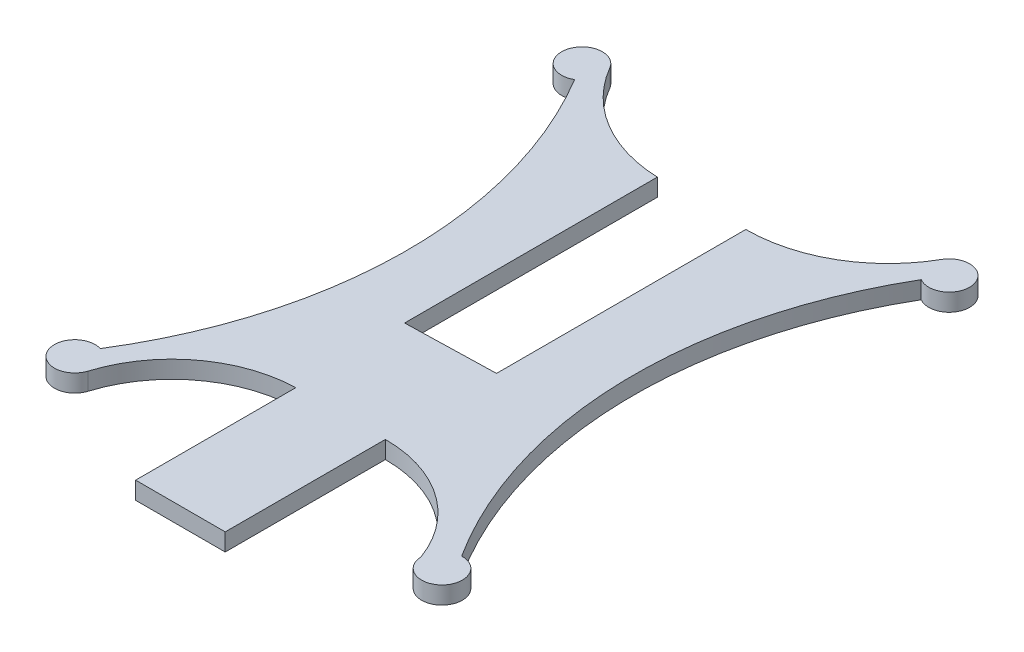
SolidWorks part; units mm, degrees
ref_plane "Front Plane" through (0, 0, 0) normal (0, 0, 1) x (1, 0, 0)
ref_plane "Top Plane" through (0, 0, 0) normal (0, 1, 0) x (1, 0, 0)
ref_plane "Right Plane" through (0, 0, 0) normal (1, 0, 0) x (0, 0, -1)
sketch "Sketch1" plane through (0, 0, 0) normal (0, 1, 0) x (1, 0, 0)
  line L0 (25.7571, -1.3519) -> (25.7571, 41.4312)
  line L1 (10.6524, -48.1898) -> (26.0304, -48.1898)
  line L2 (10.6524, -48.1898) -> (10.6524, -20.7012)
  line L4 (26.0304, -48.1898) -> (26.0304, -20.7012)
  line L5 (10.3791, -1.7519) -> (10.3791, 41.6312)
  line L6 (10.3791, -1.7519) -> (25.7571, -1.3519)
  circle A0 centre (-12.9696, 52.0435) radius 2.025
  circle A1 centre (50.0524, 52.0435) radius 2.025
  circle A2 centre (-12.9696, -35.0065) radius 2.025
  circle A3 centre (50.0524, -35.0065) radius 2.025
  arc A4 (-9.9428, 53.8008) -> (-11.2123, 49.0166) centre (-12.9696, 52.0435) ccw
  arc A5 (-11.9327, -31.6636) -> (-9.6268, -36.0434) centre (-12.9696, -35.0065) ccw
  arc A6 (47.0448, 53.8337) -> (48.2622, 49.0359) centre (50.0524, 52.0435) cw
  arc A7 (49.9272, -31.5087) -> (46.5546, -35.1316) centre (50.0524, -35.0065) cw
  arc A8 (-9.6268, -36.0434) -> (10.6524, -20.7012) centre (11.205, -42.5052) cw
  arc A10 (26.0304, -20.7012) -> (46.5546, -35.1316) centre (26.0304, -42.5122) cw
  arc A13 (-9.9428, 53.8008) -> (10.3791, 41.6312) centre (11.2196, 66.0871) ccw
  arc A15 (25.7571, 41.4312) -> (47.0448, 53.8337) centre (25.7571, 65.9015) ccw
  arc A20 (-11.2123, 49.0166) -> (-11.9327, -31.6636) centre (-77.5314, 9.2654) cw
  arc A21 (48.2622, 49.0359) -> (49.9272, -31.5087) centre (115.0792, 10.1277) ccw
  point P29 (26.8983, -20.7012)
  point P31 (11.205, -20.7012)
  point P32 (25.7571, 41.6312)
  dimension "D1" = 4.05
  dimension "D2" = 4.05
  dimension "D4" = 4.05
  dimension "D5" = 4.05
  dimension "D7" = 3.5
  dimension "D8" = 3.5
  dimension "D9" = 3.5
  dimension "D10" = 3.5
  dimension "D12" = 39
  dimension "D13" = 15.378
  dimension "D14" = 21.8109
  dimension "D15" = 27.4885
  dimension "D3" = 63.022
  dimension "D6" = 87.05
  dimension "D11" = 39.4
extrude "Boss-Extrude2" add sketch "Sketch1" along normal blind 3 contours A5 A8 L2 L1 L4 A10 A7 A21 A6 A15 L0 L6 L5 A13 A4 A20
